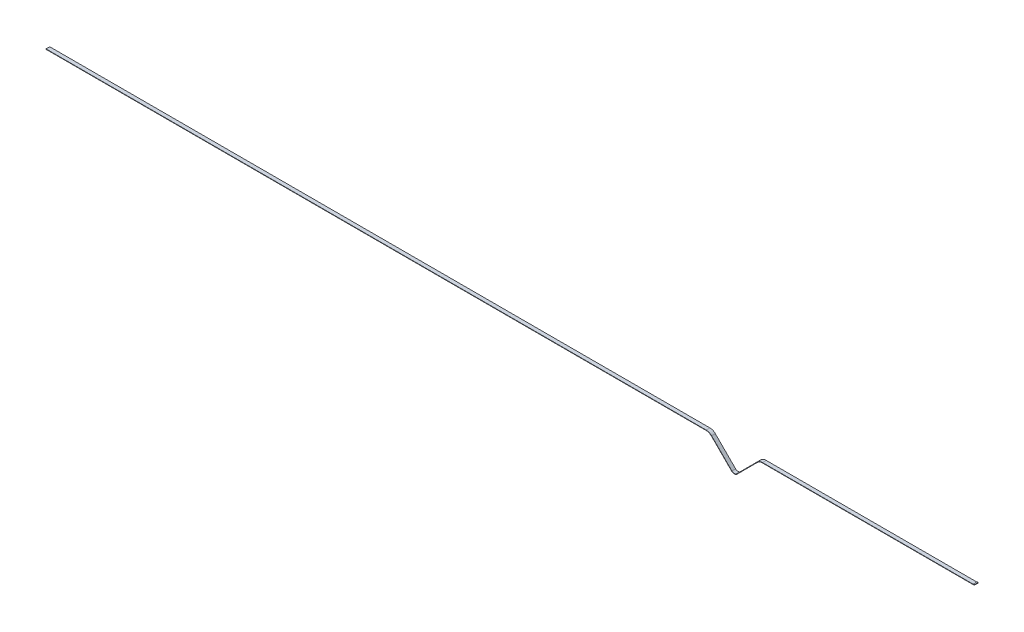
SolidWorks part; units mm, degrees
ref_plane "Front Plane" through (0, 0, 0) normal (0, 0, 1) x (1, 0, 0)
ref_plane "Top Plane" through (0, 0, 0) normal (0, 1, 0) x (1, 0, 0)
ref_plane "Right Plane" through (0, 0, 0) normal (1, 0, 0) x (0, 0, -1)
sketch "Sketch1" plane through (0, 0, 0) normal (1, 0, 0) x (0, 0, -1)
  line L1 (0, 0) -> (6, 0)
  line L2 (0, 0) -> (0, 0.63)
  line L3 (0, 0.63) -> (6, 0.63)
  line L4 (6, 0) -> (6, 0.63)
  dimension "D1" = 0.63
  dimension "D2" = 6
sketch "Sketch2" plane through (0, 0, 0) normal (0, 0, 1) x (1, 0, 0)
  line L0 (0, 0) -> (-342.2019, 0)
  line L1 (-350.657, -3.5053) -> (-383.4488, -36.3377)
  line L2 (-392.095, -36.3377) -> (-424.8867, -3.5053)
  line L3 (-433.3419, 0) -> (-1500, 0)
  arc A0 (-342.2019, 0) -> (-350.657, -3.5053) centre (-342.2019, -11.95) ccw
  arc A1 (-383.4488, -36.3377) -> (-392.095, -36.3377) centre (-387.7719, -32.02) cw
  arc A2 (-424.8867, -3.5053) -> (-433.3419, 0) centre (-433.3419, -11.95) ccw
  circle A4 centre (-387.7719, -32.02) radius 6.11 construction
  circle A6 centre (-342.2019, -11.95) radius 11.95 construction
  circle A7 centre (-433.3419, -11.95) radius 11.95 construction
  dimension "D1" = 6.11
  dimension "D4" = 1500
sweep "Sweep1" add profiles "Sketch1" path "Sketch2"
sketch "Sketch3" plane through (0, 0, 0) normal (0, 0, 1) x (1, 0, 0)
  line L0 (0, 0.63) -> (-342.2019, 0.63) construction
  line L1 (-1.5, 0.63) -> (-1.5, 0)
  line L2 (0, 0) -> (-342.2019, 0) construction
  line L3 (-1.5, 0) -> (0, 0)
  line L4 (0, 0) -> (0, 0.63)
  arc A1 (0, 0.63) -> (-1.5, 0.63) centre (-0.75, 0.63) ccw
  dimension "D1" = 0.75
extrude "Boss-Extrude1" add sketch "Sketch3" against normal through all
pattern_curve "CrvPattern1" [suppressed] parameters "D1"=2000, "D3"=2, "D2"=1, "D4"=10
